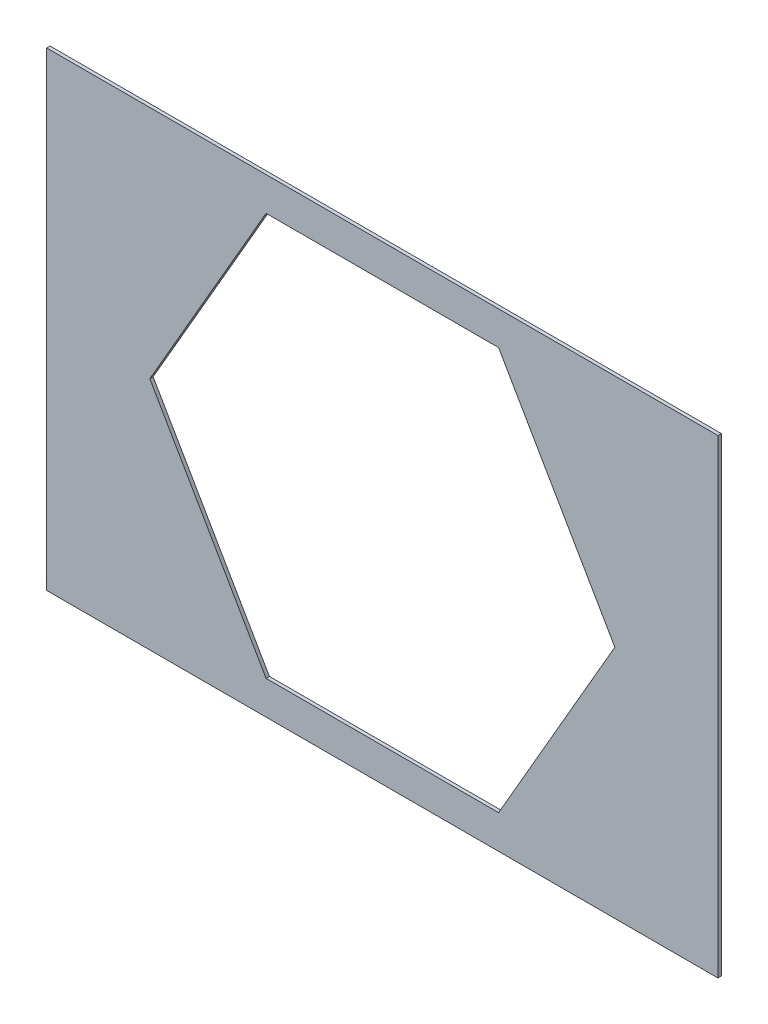
SolidWorks part; units mm, degrees
material "Pine"
ref_plane "Front Plane" through (0, 0, 0) normal (0, 0, 1) x (1, 0, 0)
ref_plane "Top Plane" through (0, 0, 0) normal (0, 1, 0) x (1, 0, 0)
ref_plane "Right Plane" through (0, 0, 0) normal (1, 0, 0) x (0, 0, -1)
sketch "Sketch1" plane through (0, 0, 0) normal (0, 0, 1) x (1, 0, 0)
  line L1 (-439.9409, 0) -> (-219.9705, -381)
  line L2 (-219.9705, -381) -> (219.9705, -381)
  line L3 (219.9705, -381) -> (439.9409, 0)
  line L4 (439.9409, 0) -> (219.9705, 381)
  line L5 (219.9705, 381) -> (-219.9705, 381)
  line L6 (-219.9705, 381) -> (-439.9409, 0)
  line L7 (635, -444.5) -> (-635, -444.5)
  line L8 (635, -444.5) -> (635, 444.5)
  line L9 (635, 444.5) -> (-635, 444.5)
  line L10 (-635, -444.5) -> (-635, 444.5)
  line L11 (635, -444.5) -> (-635, 444.5) construction
  line L12 (635, 444.5) -> (-635, -444.5) construction
  circle A0 centre (0, 0) radius 381 construction
  dimension "D1" = 762
  dimension "D2" = 1270
  dimension "D3" = 889
extrude "Boss-Extrude1" add sketch "Sketch1" along normal blind 6.35
